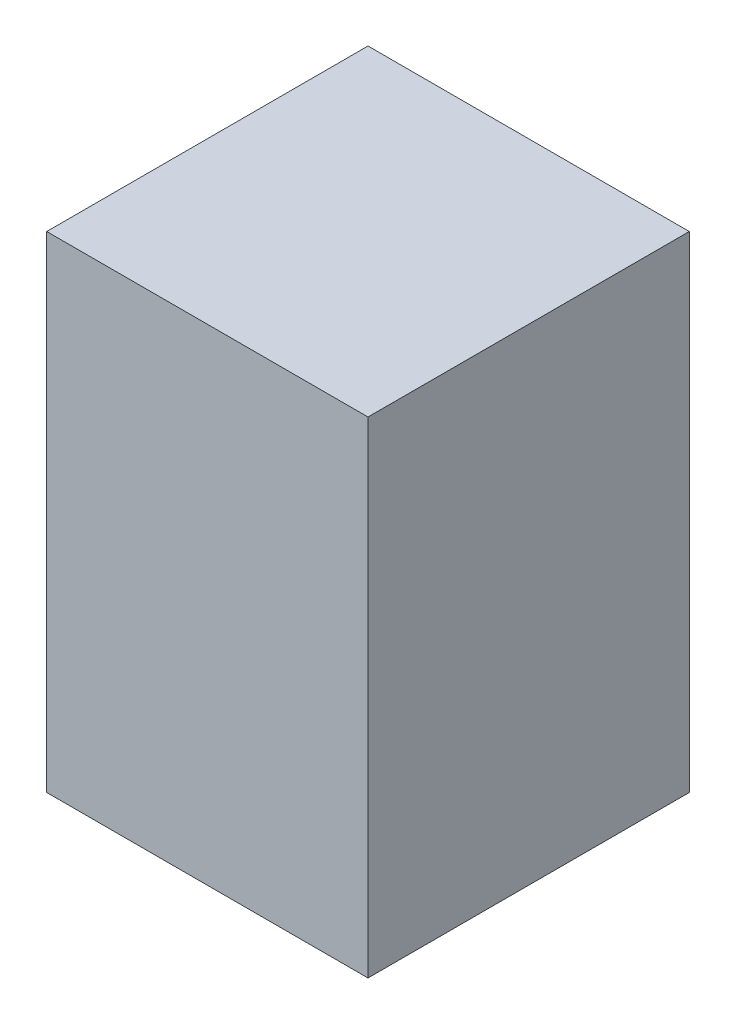
SolidWorks part; units mm, degrees
ref_plane "정면" through (0, 0, 0) normal (0, 0, 1) x (1, 0, 0)
ref_plane "윗면" through (0, 0, 0) normal (0, 1, 0) x (1, 0, 0)
ref_plane "우측면" through (0, 0, 0) normal (1, 0, 0) x (0, 0, -1)
sketch "스케치1" plane through (0, 0, 0) normal (0, 1, 0) x (1, 0, 0)
  line L1 (-41, 41) -> (41, 41)
  line L2 (-41, 41) -> (-41, -41)
  line L3 (-41, -41) -> (41, -41)
  line L4 (41, 41) -> (41, -41)
  line L5 (-41, 41) -> (41, -41) construction
  line L6 (-41, -41) -> (41, 41) construction
  point P0 (0, 0)
  dimension "D1" = 82
  dimension "D2" = 82
extrude "보스-돌출1" add sketch "스케치1" along normal blind 124
